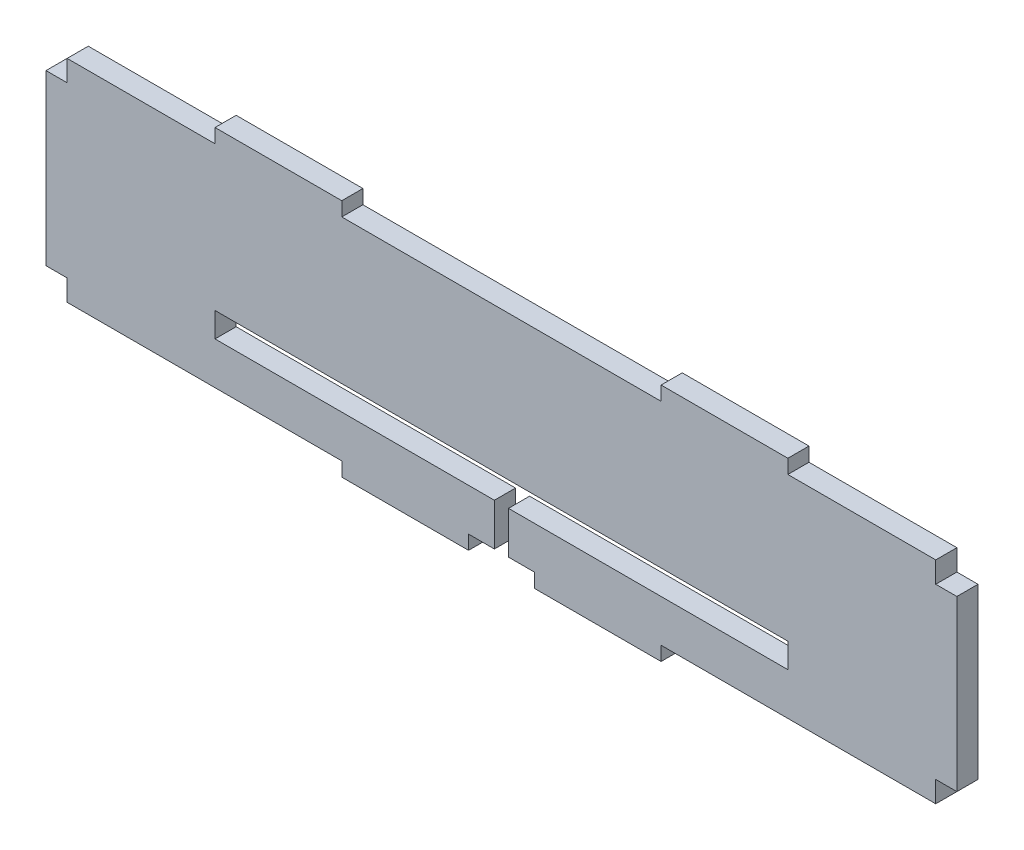
SolidWorks part; units mm, degrees
ref_plane "Front Plane" through (0, 0, 0) normal (0, 0, 1) x (1, 0, 0)
ref_plane "Top Plane" through (0, 0, 0) normal (0, 1, 0) x (1, 0, 0)
ref_plane "Right Plane" through (0, 0, 0) normal (1, 0, 0) x (0, 0, -1)
sketch "Sketch1" plane through (0, 0, 0) normal (0, 0, 1) x (1, 0, 0)
  line L0 (0, 0) -> (0, 43717.3993) construction
  line L1 (-5.9695, 0) -> (43711.4297, 0) construction
  line L2 (0, 0) -> (42, 0)
  line L4 (0, 0) -> (0, 30)
  line L6 (129.34, 0) -> (129.34, 30)
  line L7 (42, 0) -> (42, -2)
  line L8 (42, -2) -> (60, -2)
  line L9 (60, -2) -> (60, 0)
  line L10 (60, 0) -> (69.34, 0)
  line L11 (69.34, 0) -> (69.34, -2)
  line L12 (69.34, -2) -> (87.34, -2)
  line L13 (87.34, -2) -> (87.34, 0)
  line L14 (87.34, 0) -> (129.34, 0)
  line L15 (64.67, 0) -> (64.67, -50000) construction
  line L16 (24, 9.5) -> (105.34, 9.5)
  line L17 (24, 9.5) -> (24, 6)
  line L19 (105.34, 9.5) -> (105.34, 6)
  line L20 (65.67, 0) -> (65.67, 6)
  line L21 (63.67, 0) -> (65.67, 0)
  line L22 (63.67, 0) -> (63.67, 6)
  line L25 (24, 6) -> (63.67, 6)
  line L26 (65.67, 6) -> (105.34, 6)
  line L27 (0, 30) -> (24, 30)
  line L29 (42, 30) -> (42, 32)
  line L30 (42, 32) -> (24, 32)
  line L31 (24, 30) -> (24, 32)
  line L32 (42, 30) -> (87.34, 30)
  line L33 (129.34, 30) -> (105.34, 30)
  line L34 (105.34, 30) -> (105.34, 32)
  line L35 (87.34, 32) -> (105.34, 32)
  line L36 (87.34, 30) -> (87.34, 32)
  line L37 (129.34, 3) -> (126.34, 3)
  line L38 (0, 0) -> (3, 0)
  line L39 (0, 0) -> (0, 3)
  line L40 (0, 3) -> (3, 3)
  line L41 (3, 0) -> (3, 3)
  line L42 (126.34, 0) -> (126.34, 3)
  line L43 (129.34, 0) -> (126.34, 0)
  line L44 (129.34, 0) -> (129.34, 3)
  line L45 (-14.82, 15) -> (49985.18, 15) construction
  line L46 (129.34, 30) -> (126.34, 30)
  line L47 (126.34, 30) -> (126.34, 27)
  line L48 (129.34, 27) -> (126.34, 27)
  line L49 (129.34, 30) -> (129.34, 27)
  line L50 (0, 27) -> (3, 27)
  line L51 (3, 30) -> (3, 27)
  line L52 (0, 30) -> (3, 30)
  line L53 (0, 30) -> (0, 27)
  point P36 (64.67, 30)
  dimension "D15" = 3
  dimension "D1" = 129.34
  dimension "D2" = 30
  dimension "D3" = 18
  dimension "D4" = 18
  dimension "D5" = 42
  dimension "D6" = 42
  dimension "D7" = 2
  dimension "D8" = 2
  dimension "D9" = 24
  dimension "D10" = 24
  dimension "D11" = 6
  dimension "D12" = 3.5
  dimension "D13" = 15
  dimension "D14" = 2
  dimension "D16" = 21
  dimension "D17" = 18
  dimension "D18" = 45.34
  dimension "D19" = 18
  dimension "D20" = 21
  dimension "D21" = 3
  dimension "D22" = 3
  dimension "D23" = 2
  dimension "D24" = 3
  dimension "D25" = 9.34
extrude "Boss-Extrude3" add sketch "Sketch1" along normal blind 3 contours L36 L32 L29 L30 L31 L27 L4 L2 L7 L8 L9 L10 L22 L25 L17 L16 L19 L26 L20 L11 L12 L13 L14 L6 L33 L34 L35
